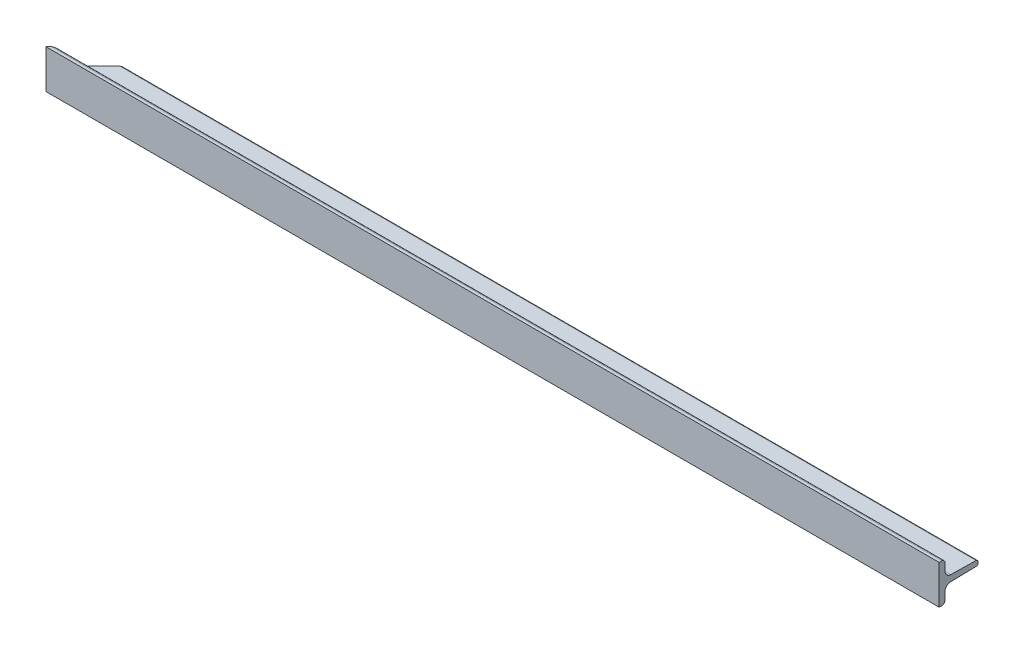
SolidWorks part; units mm, degrees
ref_plane "Front Plane" through (0, 0, 0) normal (0, 0, 1) x (1, 0, 0)
ref_plane "Top Plane" through (0, 0, 0) normal (0, 1, 0) x (1, 0, 0)
ref_plane "Right Plane" through (0, 0, 0) normal (1, 0, 0) x (0, 0, -1)
sketch "Sketch1" plane through (0, 0, 0) normal (0, 0, 1) x (1, 0, 0)
  line L0 (0, 0) -> (460, 0)
  point P4 (0, 0)
  dimension "D1" = 460
other "T section T 20 X 20(1)"
ref_plane "Plane1" through (0, 0, 0) normal (1, 0, 0) x (0, 1, 0)
sketch "Sketch12" plane through (0, 0, 0) normal (1, 0, 0) x (0, 1, 0)
  line L0 (-10, 20) -> (10, 20)
  line L2 (-1.3196, 0.98) -> (-1.581, 14.051)
  line L3 (-4.5204, 16.9904) -> (-8.53, 17.0706)
  line L5 (-10, 20) -> (-10, 18.5703)
  line L6 (10, 20) -> (10, 18.5703)
  line L7 (8.53, 17.0706) -> (4.5204, 16.9904)
  line L8 (1.581, 14.051) -> (1.3196, 0.98)
  line L9 (-5, 17) -> (5, 17) construction
  line L10 (0, 20) -> (0, 0) construction
  line L12 (-0.3198, 0) -> (0.3198, 0)
  arc A0 (-8.53, 17.0706) -> (-10, 18.5703) centre (-8.5, 18.5703) cw
  arc A1 (8.53, 17.0706) -> (10, 18.5703) centre (8.5, 18.5703) ccw
  arc A2 (-1.581, 14.051) -> (-4.5204, 16.9904) centre (-4.5804, 13.991) ccw
  arc A3 (4.5204, 16.9904) -> (1.581, 14.051) centre (4.5804, 13.991) ccw
  arc A4 (-0.3198, 0) -> (-1.3196, 0.98) centre (-0.3198, 1) cw
  arc A5 (1.3196, 0.98) -> (0.3198, 0) centre (0.3198, 1) cw
  point P16 (10, 17.1)
  point P24 (-1.3, 0)
  point P27 (1.3, 0)
  point P28 (0, 0)
  dimension "D2" = 1.146
  dimension "R2" = 1.5
  dimension "R1" = 3
  dimension "R3" = 1
  dimension "D1" = 1.146
  dimension "D3" = 2.9
  dimension "BF" = 20
  dimension "DEPTH" = 20
  dimension "TF" = 3
  dimension "D4" = 2.5999
  dimension "D5" = 1.146
ref_plane "Plane2" through (10, 0, 10) normal (-0.7071, 0, -0.7071) x (0, -1, 0)
sketch "Sketch13" plane through (10, 0, 10) normal (-0.7071, 0, -0.7071) x (0, -1, 0)
  line L1 (-10, -15) -> (10, -15)
  line L2 (-10, -15) -> (-10, 15)
  line L3 (-10, 15) -> (10, 15)
  line L4 (10, -15) -> (10, 15)
  line L5 (-10, -15) -> (10, 15) construction
  line L6 (-10, 15) -> (10, -15) construction
  point P0 (0, 0)
  dimension "D1" = 30
  dimension "D2" = 20
extrude "Cut-Extrude1" cut sketch "Sketch13" along normal through all
